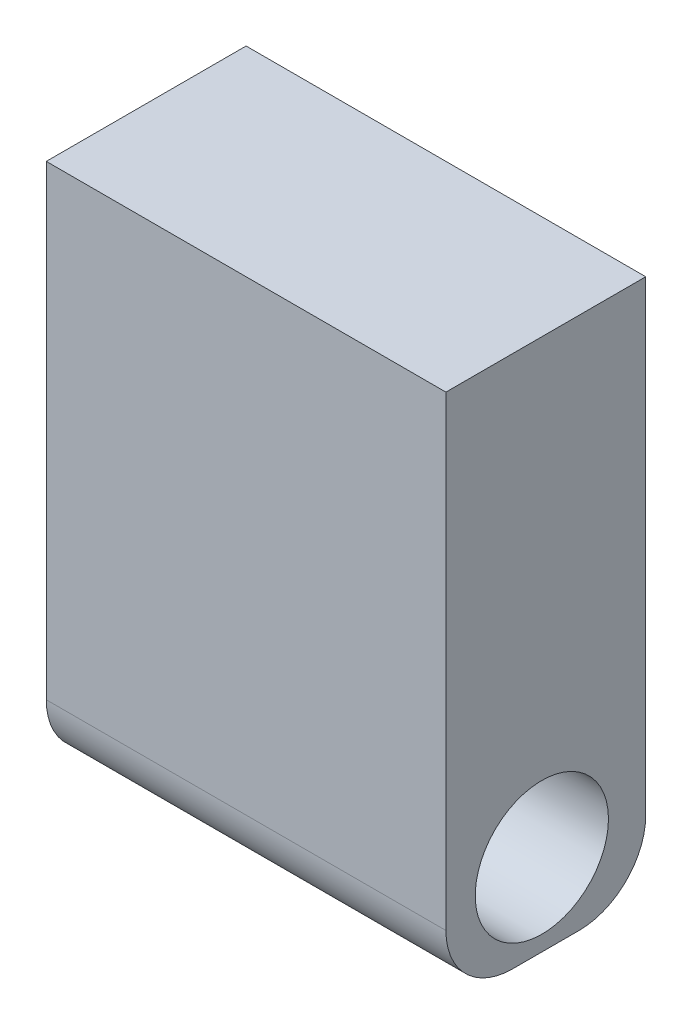
SolidWorks part; units mm, degrees
ref_plane "Front Plane" through (0, 0, 0) normal (0, 0, 1) x (1, 0, 0)
ref_plane "Top Plane" through (0, 0, 0) normal (0, 1, 0) x (1, 0, 0)
ref_plane "Right Plane" through (0, 0, 0) normal (1, 0, 0) x (0, 0, -1)
sketch "Sketch1" plane through (0, 0, 0) normal (0, 0, 1) x (1, 0, 0)
  line L0 (0, 0) -> (0, 258.1535) construction
  line L2 (286.7933, 0) -> (256.7933, 0)
  line L3 (286.7933, 0) -> (286.7933, 40)
  line L4 (286.7933, 40) -> (256.7933, 40)
  line L5 (256.7933, 0) -> (256.7933, 40)
  dimension "D1" = 40
  dimension "D2" = 30
extrude "Boss-Extrude2" add sketch "Sketch1" along normal blind 15
fillet "Fillet4" radius 5 1 edges at (271.7933, 0, 15)
fillet "Fillet5" radius 5 1 edges at (271.7933, 0, 0)
sketch "Sketch3" plane through (286.7933, 0, 0) normal (1, 0, 0) x (0, 0, -1)
  circle A0 centre (-7.7986, 6.154) radius 5
  dimension "D1" = 10
extrude "Cut-Extrude2" cut sketch "Sketch3" against normal through all
